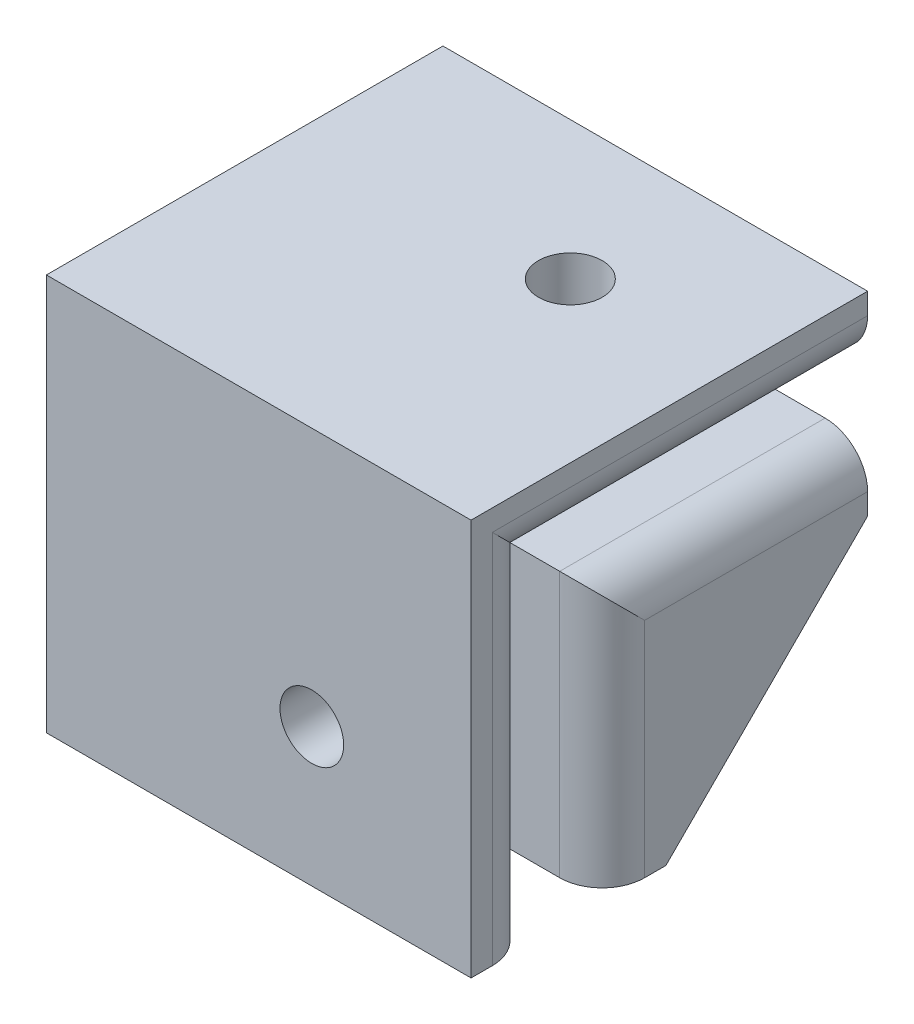
SolidWorks part; units mm, degrees
ref_plane "Front Plane" through (0, 0, 0) normal (0, 0, 1) x (1, 0, 0)
ref_plane "Top Plane" through (0, 0, 0) normal (0, 1, 0) x (1, 0, 0)
ref_plane "Right Plane" through (0, 0, 0) normal (1, 0, 0) x (0, 0, -1)
sketch "Sketch1" plane through (0, 0, 0) normal (1, 0, 0) x (0, 0, -1)
  line L0 (0, 0) -> (0, -12.5) construction
  line L1 (0, -12.5) -> (-3.175, -12.5)
  line L2 (-3.175, -12.5) -> (-3.175, 3.175) construction
  line L3 (-3.175, 3.175) -> (12.5, 3.175) construction
  line L4 (12.5, 3.175) -> (12.5, 0)
  line L5 (12.5, 0) -> (0, 0) construction
  line L6 (0, -12.5) -> (3, -12.5)
  line L7 (3, -12.5) -> (12.5, -3)
  line L8 (12.5, -3) -> (12.5, 0)
  line L9 (12.5, 3.175) -> (12.5, 6.175)
  line L10 (12.5, 6.175) -> (-6.175, 6.175)
  line L11 (-6.175, 6.175) -> (-6.175, -12.5)
  line L12 (-6.175, -12.5) -> (-3.175, -12.5)
  dimension "D1" = 3.175
  dimension "D2" = 3.175
  dimension "D3" = 12.5
  dimension "D4" = 12.5
  dimension "D5" = 3
  dimension "D6" = 3
  dimension "D7" = 3
  dimension "D8" = 3
extrude "Boss-Extrude1" add sketch "Sketch1" along normal blind 20
sketch "Sketch2" plane through (20, 0, 0) normal (1, 0, 0) x (0, 0, -1)
  line L0 (-3.175, -12.5) -> (0, -12.5)
  line L1 (0, -12.5) -> (0, 0)
  line L2 (0, 0) -> (12.5, 0)
  line L3 (12.5, 0) -> (12.5, 3.175)
  line L4 (12.5, 3.175) -> (-3.175, 3.175)
  line L5 (-3.175, 3.175) -> (-3.175, -12.5)
extrude "Cut-Extrude1" cut sketch "Sketch2" against normal blind 15
fillet "Fillet1" radius 2 4 edges at (20, -4.6625, 3.175) (20, -6.25, 0) (20, 0, -6.25) (20, 3.175, -4.6625)
sketch "Sketch3" plane through (0, 6.175, 0) normal (0, 1, 0) x (1, 0, 0)
  line L0 (5, 12.5) -> (5, -6.175) construction
  line L1 (20, 12.5) -> (0, 12.5) construction
  line L2 (20, -6.175) -> (0, -6.175) construction
  line L3 (0, 12.5) -> (0, -6.175) construction
  line L4 (5, 6) -> (20, 6) construction
  line L5 (5, -3.175) -> (20, -3.175) construction
  line L6 (20, 12.5) -> (20, -6.175) construction
  line L7 (5, 0) -> (20, 0) construction
  line L8 (5, 3) -> (20, 3) construction
  circle A0 centre (12.5, 6) radius 1.5
  dimension "D2" = 3
  dimension "D1" = 5
  dimension "D3" = 3
  dimension "D4" = 3.175
  dimension "D5" = 3
  dimension "D6" = 6
extrude "Cut-Extrude2" cut sketch "Sketch3" against normal through all
sketch "Sketch4" plane through (0, 0, 6.175) normal (0, 0, 1) x (1, 0, 0)
  line L0 (5, 6.175) -> (5, -12.5) construction
  line L1 (20, 6.175) -> (0, 6.175) construction
  line L2 (20, -12.5) -> (0, -12.5) construction
  line L3 (0, 6.175) -> (0, -12.5) construction
  line L4 (20, -6) -> (5, -6) construction
  circle A0 centre (12.5, -6) radius 1.5
  dimension "D2" = 3
  dimension "D1" = 5
  dimension "D3" = 12.175
extrude "Cut-Extrude3" cut sketch "Sketch4" against normal through all
